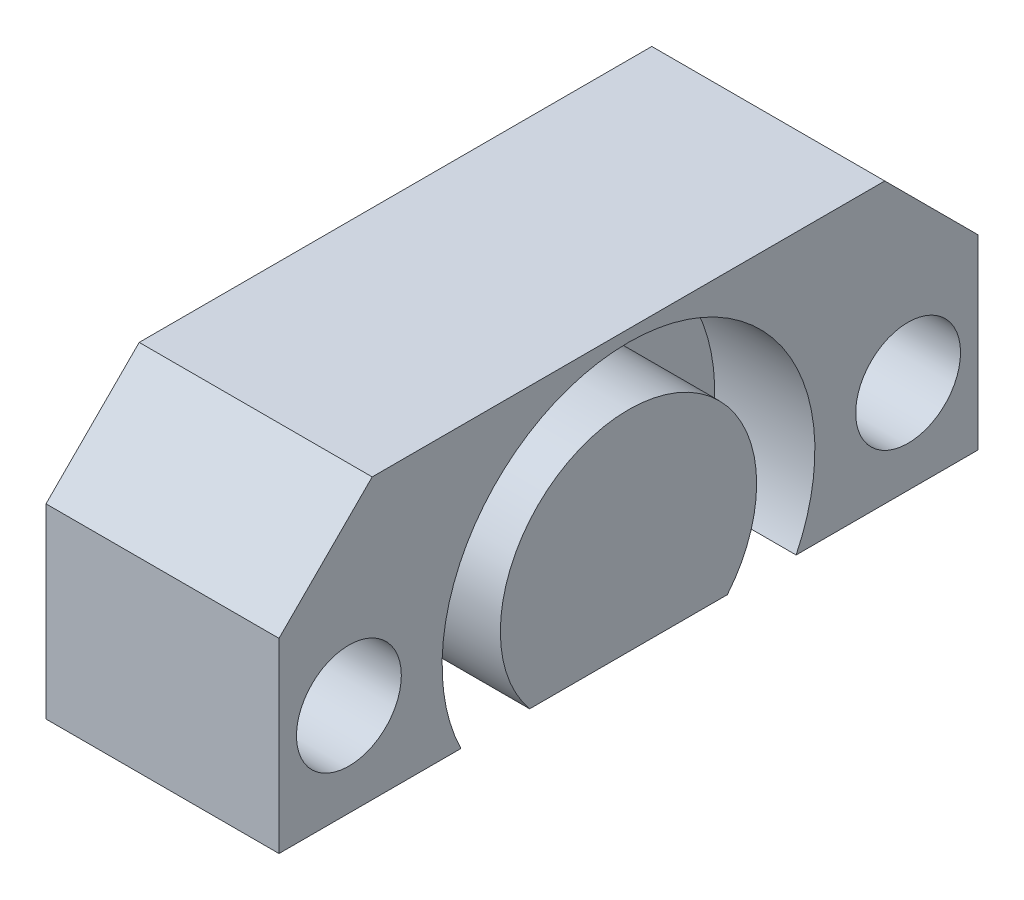
SolidWorks part; units mm, degrees
material "Printed PLA"
ref_plane "Front Plane" through (0, 0, 0) normal (0, 0, 1) x (1, 0, 0)
ref_plane "Top Plane" through (0, 0, 0) normal (0, 1, 0) x (1, 0, 0)
ref_plane "Right Plane" through (0, 0, 0) normal (1, 0, 0) x (0, 0, -1)
sketch "Sketch1" plane through (0, 0, 0) normal (1, 0, 0) x (0, 0, -1)
  line L0 (-15, 0) -> (15, 0)
  line L1 (15, 0) -> (15, 8)
  line L2 (15, 8) -> (11, 12)
  line L3 (11, 12) -> (-11, 12)
  line L4 (-11, 12) -> (-15, 8)
  line L5 (-15, 8) -> (-15, 0)
  line L6 (0, 0) -> (0, 12) construction
  dimension "D1" = 30
  dimension "D2" = 4
  dimension "D3" = 12
extrude "Boss-Extrude1" add sketch "Sketch1" along normal blind 10
sketch "Sketch2" plane through (10, 0, 0) normal (1, 0, 0) x (0, 0, -1)
  line L0 (11, 12) -> (-11, 12) construction
  line L1 (0, 3.5) -> (0, 0) construction
  circle A0 centre (0, 3.5) radius 8
  circle A1 centre (0, 3.5) radius 5.5
  dimension "D1" = 16
  dimension "D3" = 2.5
  dimension "D2" = 8.5
extrude "Cut-Extrude2" cut sketch "Sketch2" against normal blind 4.3
sketch "Sketch3" plane through (10, 0, 0) normal (1, 0, 0) x (0, 0, -1)
  line L0 (12, 4) -> (-12, 4) construction
  line L1 (0, 4) -> (0, 0) construction
  line L2 (11, 12) -> (-11, 12) construction
  circle A0 centre (-12, 4) radius 2.25
  circle A1 centre (12, 4) radius 2.25
  dimension "D3" = 4.5
  dimension "D1" = 24
  dimension "D2" = 8
extrude "Cut-Extrude3" cut sketch "Sketch3" against normal through all
